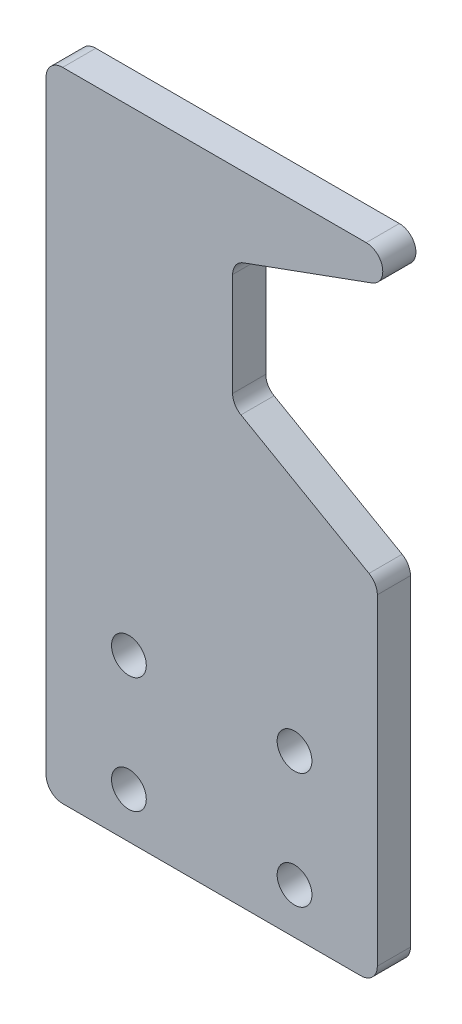
SolidWorks part; units mm, degrees
material "Thornel Mat VMA"
ref_plane "前视基准面" through (0, 0, 0) normal (0, 0, 1) x (1, 0, 0)
ref_plane "上视基准面" through (0, 0, 0) normal (0, 1, 0) x (1, 0, 0)
ref_plane "右视基准面" through (0, 0, 0) normal (1, 0, 0) x (0, 0, -1)
other "Configuration Table"
sketch "草图1" plane through (0, 0, 0) normal (0, 0, 1) x (1, 0, 0)
  line L0 (-20, 56) -> (-20, 21)
  line L2 (-20, 21) -> (-20, -21)
  line L3 (-20, -21) -> (20, -21)
  line L4 (20, 21) -> (20, -21)
  line L5 (-20, 21) -> (20, -21) construction
  line L6 (-20, -21) -> (20, 21) construction
  line L7 (-20, 21) -> (-5.963, 21)
  line L8 (-20, 56) -> (18.6574, 56)
  line L10 (19.3415, 52.1206) -> (2.5252, 46)
  line L11 (2.5252, 46) -> (2.5252, 31)
  line L12 (2.5252, 31) -> (20, 21)
  arc A0 (18.6574, 56) -> (19.3415, 52.1206) centre (18.6574, 54) cw
  point P0 (0, 0)
  point P19 (30, 56)
  dimension "D8" = 10
  dimension "D7" = 2
  dimension "D1" = 40
  dimension "D2" = 42
  dimension "D3" = 90
  dimension "D4" = 35
  dimension "D5" = 50
  dimension "D6" = 15
  dimension "D9" = 20
extrude "凸台-拉伸1" add sketch "草图1" along normal blind 4
sketch "草图2" plane through (0, 0, 4) normal (0, 0, 1) x (1, 0, 0)
  line L1 (-20, -21) -> (20, -21) construction
  line L2 (0, -21) -> (0, -4.5877) construction
  circle A0 centre (-10, -15.5) radius 2.1
  circle A1 centre (-10, -1.5) radius 2.1
  circle A2 centre (10, -1.5) radius 2.1
  circle A3 centre (10, -15.5) radius 2.1
  dimension "D2" = 5.5
  dimension "D1" = 4.2
  dimension "D3" = 20
  dimension "D5" = 14
extrude "切除-拉伸1" cut sketch "草图2" against normal up to next
sketch "草图3" plane through (0, 0, 4) normal (0, 0, 1) x (1, 0, 0)
  line L1 (20, 21) -> (20, -21) construction
  circle A2 centre (-0.5, 14.8805) radius 10.5 construction
  circle A3 centre (10, 14.8805) radius 2.25
  circle A10 centre (-5.75, 5.7872) radius 2.25
  circle A11 centre (-5.75, 23.9738) radius 2.25
  point P13 (-0.5, 14.8805)
  dimension "D1" = 21
  dimension "D2" = 4.5
  dimension "D3" = 3
  dimension "D4" = 10
fillet "圆角1" radius 2 6 edges at (-20, 56, 2) (20, 21, 2) (20, -21, 2) (-20, -21, 2) (2.5252, 46, 2) (2.5252, 31, 2)
